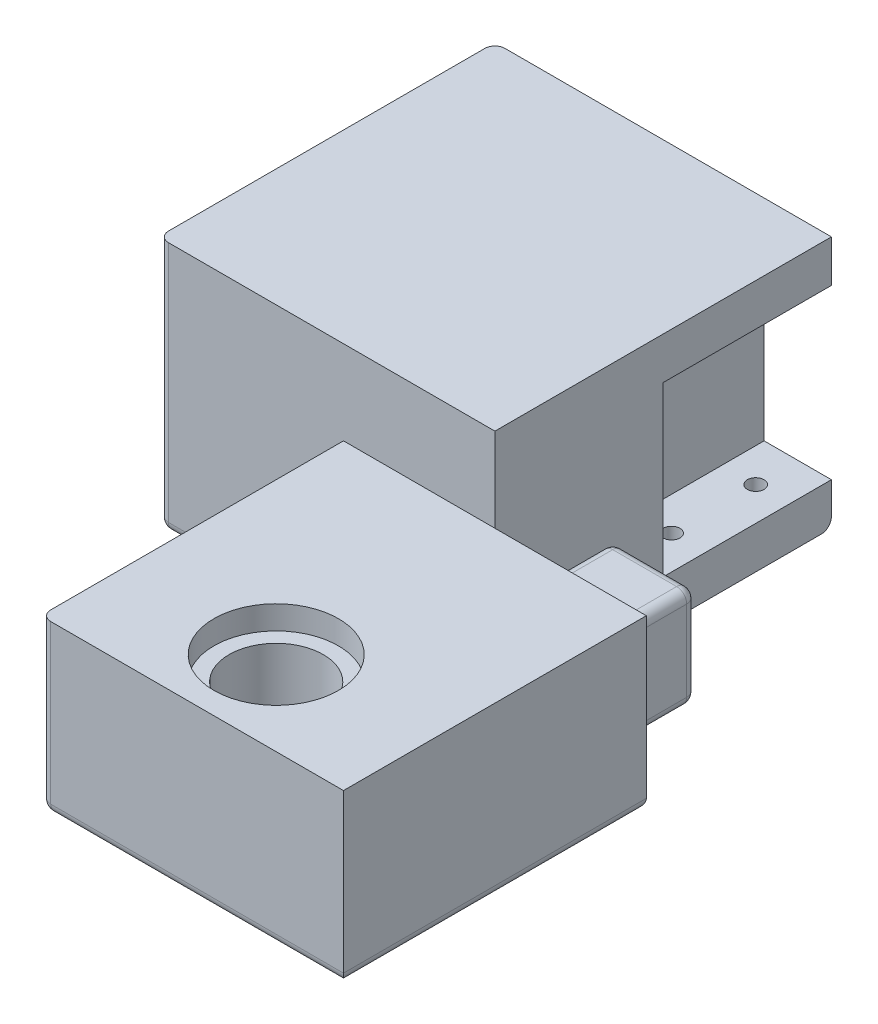
SolidWorks part; units mm, degrees
ref_plane "Front Plane" through (0, 0, 0) normal (0, 0, 1) x (1, 0, 0)
ref_plane "Top Plane" through (0, 0, 0) normal (0, 1, 0) x (1, 0, 0)
ref_plane "Right Plane" through (0, 0, 0) normal (1, 0, 0) x (0, 0, -1)
sketch "Sketch1" plane through (0, 0, 0) normal (0, 1, 0) x (1, 0, 0)
  line L0 (0, 0) -> (-133401.8874, 0) construction
  line L1 (0, 0) -> (0, -133401.8874) construction
  line L3 (-50, 50) -> (50, 50)
  line L4 (-50, 50) -> (-50, -50)
  line L5 (-50, -50) -> (50, -50)
  line L6 (50, 50) -> (50, -50)
  line L7 (-50, 50) -> (50, -50) construction
  line L8 (-50, -50) -> (50, 50) construction
  point P5 (0, 0)
  dimension "D1" = 100
  dimension "D2" = 100
extrude "Boss-Extrude1" add sketch "Sketch1" along normal blind 50
sketch "Sketch8" plane through (0, 50, 0) normal (0, 1, 0) x (1, 0, 0)
  line L0 (0, 0) -> (-50000, 0) construction
  line L1 (0, 0) -> (0, -50000) construction
  line L2 (-50, -50) -> (50, -50) construction
  line L3 (5, -140) -> (95, -140)
  line L4 (5, -140) -> (5, -50)
  line L5 (5, -50) -> (95, -50)
  line L6 (95, -140) -> (95, -50)
  line L7 (5, -140) -> (95, -50) construction
  line L8 (5, -50) -> (95, -140) construction
  line L9 (-50, 50) -> (-50, -50) construction
  point P5 (50, -95)
  dimension "D1" = 90
  dimension "D2" = 90
  dimension "D3" = 100
extrude "Boss-Extrude4" add sketch "Sketch8" against normal up to surface (50 mm away) up to face at (0, 0, 0)
sketch "Sketch9" plane through (0, 50, 0) normal (0, 1, 0) x (1, 0, 0)
  line L0 (-50, 50) -> (-50, -50) construction
  line L1 (0, 0) -> (-50000, 0) construction
  line L3 (-50, -50) -> (5, -50) construction
  line L4 (0, 0) -> (0, -50000) construction
  circle A0 centre (50, -115) radius 18.5
  dimension "D1" = 37
  dimension "D2" = 65
  dimension "D3" = 100
extrude "Cut-Extrude1" cut sketch "Sketch9" against normal blind 7
sketch "Sketch10" plane through (0, 50, 0) normal (0, 1, 0) x (1, 0, 0)
  line L0 (0, 0) -> (-50000, 0) construction
  line L1 (0, 0) -> (0, -50000) construction
  circle A0 centre (50, -115) radius 14
  dimension "D1" = 28
extrude "Cut-Extrude2" cut sketch "Sketch10" against normal blind 25
sketch "Sketch11" plane through (0, 0, 50) normal (0, 0, -1) x (-1, 0, 0)
  line L0 (-95, 25) -> (49905, 25) construction
  line L1 (-95, 0) -> (-95, 50) construction
  line L2 (0, 0) -> (0, -50000) construction
  line L3 (-50, 0) -> (50, 0) construction
  line L4 (-72.5, 50) -> (-72.5, -49950) construction
  line L5 (-95, 50) -> (-50, 50) construction
  line L11 (-85, 10) -> (-60, 10)
  line L12 (-85, 10) -> (-85, 40)
  line L13 (-85, 40) -> (-60, 40)
  line L14 (-60, 10) -> (-60, 40)
  line L15 (-85, 10) -> (-60, 40) construction
  line L16 (-85, 40) -> (-60, 10) construction
  point P4 (-95, 25)
  point P9 (0, 0)
  point P14 (-72.5, 50)
  point P15 (-72.5, 25)
  dimension "D1" = 25
  dimension "D2" = 30
extrude "Boss-Extrude5" add sketch "Sketch11" along normal blind 25
sketch "Sketch12" plane through (0, 50, 0) normal (0, 1, 0) x (1, 0, 0)
  line L0 (0, 0) -> (-50000, 0) construction
  line L1 (0, 0) -> (0, -50000) construction
  line L3 (-50, 50) -> (50, 50)
  line L4 (-50, 50) -> (-50, -50)
  line L5 (-50, -50) -> (50, -50)
  line L6 (50, 50) -> (50, -50)
  line L7 (-50, 50) -> (50, -50) construction
  line L8 (-50, -50) -> (50, 50) construction
  point P5 (0, 0)
extrude "Boss-Extrude6" add sketch "Sketch12" along normal blind 25
sketch "Sketch13" plane through (0, 0, -50) normal (0, 0, -1) x (-1, 0, 0)
  line L0 (0, 0) -> (0, -50000) construction
  line L1 (-50, 0) -> (50, 0) construction
  line L2 (50, 37.5) -> (-49950, 37.5) construction
  line L3 (50, 75) -> (50, 0) construction
  line L4 (-50, 50) -> (-50, 0) construction
  line L5 (-30, 62.5) -> (-50, 62.5)
  line L6 (-30, 62.5) -> (-30, 12.5)
  line L7 (-30, 12.5) -> (-50, 12.5)
  line L8 (-50, 62.5) -> (-50, 12.5)
  line L9 (-30, 62.5) -> (-50, 12.5) construction
  line L10 (-30, 12.5) -> (-50, 62.5) construction
  point P4 (0, 0)
  point P9 (50, 37.5)
  point P10 (-40, 37.5)
  dimension "D1" = 20
  dimension "D2" = 50
extrude "Cut-Extrude3" cut sketch "Sketch13" against normal blind 50
sketch "Sketch14" plane through (0, 10, 0) normal (0, -1, 0) x (1, 0, 0)
  line L0 (0, 0) -> (-50000, 0) construction
  line L1 (0, 0) -> (0, -50000) construction
  line L2 (60, 37.5) -> (50060, 37.5) construction
  line L3 (60, 25) -> (60, 50) construction
  line L4 (72.5, 50) -> (72.5, -49950) construction
  line L5 (50, 50) -> (95, 50) construction
  circle A0 centre (72.5, 37.5) radius 2
  point P9 (60, 37.5)
  point P14 (72.5, 50)
  dimension "D1" = 4
extrude "Cut-Extrude4" cut sketch "Sketch14" against normal blind 15
sketch "Sketch15" plane through (0, 0, 0) normal (0, -1, 0) x (1, 0, 0)
  line L0 (0, 0) -> (50000, 0) construction
  line L1 (0, 0) -> (0, -50000) construction
  line L2 (40, -50) -> (40, -50050) construction
  line L4 (50, 50) -> (50, -50) construction
  line L5 (40, -25) -> (-49960, -25) construction
  line L6 (50, -50) -> (-50, -50) construction
  circle A0 centre (40, -37.5) radius 2.5
  circle A1 centre (40, -12.5) radius 2.5
  dimension "D3" = 5
  dimension "D4" = 12.5
  dimension "D1" = 10
  dimension "D2" = 25
extrude "Cut-Extrude5" cut sketch "Sketch15" against normal blind 15
sketch "Sketch16" plane through (0, 0, 0) normal (0, -1, 0) x (1, 0, 0)
  line L0 (0, 0) -> (-43183.8141, 0) construction
  line L1 (40, -12.5) -> (40, -50012.5) construction
  line L2 (0, 0) -> (0, -50000) construction
  line L4 (4.705, -25) -> (-43179.1091, -25) construction
  line L5 (50, -50) -> (-50, -50) construction
  circle A1 centre (40, -12.5) radius 3.75
  circle A2 centre (40, -37.5) radius 3.75
  dimension "D2" = 7.5
  dimension "D1" = 25
extrude "Cut-Extrude6" cut sketch "Sketch16" against normal blind 4
fillet "Fillet1" radius 3 18 edges at (50, 0, 140) (5, 25, 140) (5, 0, 95) (-22.5, 0, 50) (-50, 37.5, 50) (-50, 0, 0) (0, 0, -50) (-50, 37.5, -50) (85, 25, 25) (72.5, 10, 25) (60, 25, 25) (72.5, 40, 25) (60, 40, 37.5) (60, 10, 37.5) (85, 10, 37.5) (85, 40, 37.5) (95, 0, 95) (72.5, 0, 50)
